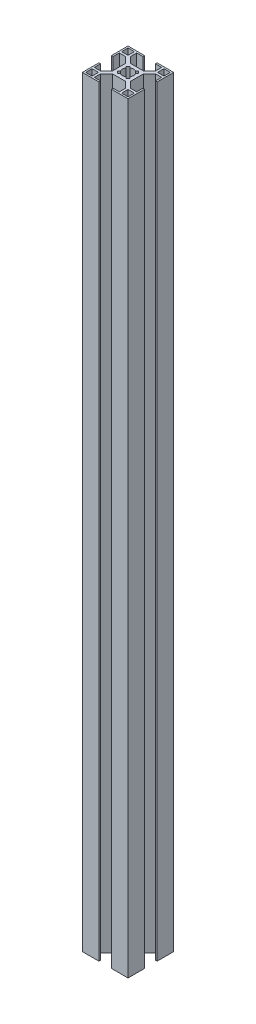
SolidWorks part; units mm, degrees
material "3.0255 (EN-AW 1350A)"
ref_plane "Alzado" through (0, 0, 0) normal (0, 0, 1) x (1, 0, 0)
ref_plane "Planta" through (0, 0, 0) normal (0, 1, 0) x (1, 0, 0)
ref_plane "Vista lateral" through (0, 0, 0) normal (1, 0, 0) x (0, 0, -1)
sketch "Croquis2" plane through (0, 0, 0) normal (0, 1, 0) x (1, 0, 0)
  line L0 (-12.6732, 23.1711) -> (-8.4732, 23.1711)
  line L1 (-37.3732, 24.2711) -> (-26.4982, 24.2711)
  line L2 (-37.3732, 24.2711) -> (-37.3732, 13.3961)
  line L3 (-37.3732, -5.7289) -> (-26.4982, -5.7289)
  line L4 (-7.3732, 24.2711) -> (-7.3732, 13.3961)
  line L5 (-30.5732, -4.6289) -> (-26.4982, -4.6289)
  line L6 (-30.5732, 23.1711) -> (-26.4982, 23.1711)
  line L7 (-36.2732, 5.1461) -> (-37.3732, 5.1461)
  line L8 (-8.4732, 23.1711) -> (-8.4732, 18.9711)
  line L9 (-36.2732, -4.6289) -> (-32.0732, -4.6289)
  line L10 (-36.2732, 23.1711) -> (-36.2732, 18.9711)
  line L11 (-36.2732, 23.1711) -> (-32.0732, 23.1711)
  line L12 (-32.0732, -0.4289) -> (-36.2732, -0.4289)
  line L15 (-8.4732, 18.9711) -> (-12.6732, 18.9711)
  line L16 (-12.6732, 23.1711) -> (-12.6732, 18.9711)
  line L17 (-32.0732, -0.4289) -> (-32.0732, -4.6289)
  line L19 (-36.2732, -0.4289) -> (-36.2732, -4.6289)
  line L21 (-32.0732, 23.1711) -> (-32.0732, 18.9711)
  line L22 (-32.0732, 18.9711) -> (-36.2732, 18.9711)
  line L24 (-8.4732, -0.4289) -> (-12.6732, -0.4289)
  line L25 (-8.4732, -0.4289) -> (-8.4732, -4.6289)
  line L26 (-8.4732, -4.6289) -> (-12.6732, -4.6289)
  line L27 (-12.6732, -0.4289) -> (-12.6732, -4.6289)
  line L28 (-26.5862, 3.3611) -> (-18.1603, 3.3611)
  line L29 (-16.4632, 13.4841) -> (-16.4632, 5.0582)
  line L30 (-26.5862, 15.1811) -> (-18.1603, 15.1811)
  line L31 (-28.2832, 13.4841) -> (-28.2832, 5.0582)
  line L32 (-28.2832, 15.1811) -> (-16.4632, 15.1811) construction
  line L33 (-28.2832, 3.3611) -> (-16.4632, 3.3611) construction
  line L34 (-7.3732, 5.1461) -> (-8.4732, 5.1461)
  line L35 (-7.3732, 13.3961) -> (-8.4732, 13.3961)
  line L36 (-26.4982, 24.2711) -> (-26.4982, 23.1711)
  line L37 (-18.2482, 24.2711) -> (-18.2482, 23.1711)
  line L38 (-36.2732, 13.3961) -> (-37.3732, 13.3961)
  line L39 (-19.1655, 11.0646) -> (-18.2482, 11.9819)
  line L40 (-36.2732, 5.1461) -> (-36.2732, 1.0711)
  line L41 (-36.2732, 23.1711) -> (-36.2732, -4.6289) construction
  line L42 (-37.3732, 5.1461) -> (-37.3732, -5.7289)
  line L43 (-37.3732, 24.2711) -> (-37.3732, -5.7289) construction
  line L44 (-18.2482, -4.6289) -> (-18.2482, -5.7289)
  line L46 (-8.4732, 5.1461) -> (-8.4732, 1.0711)
  line L47 (-8.4732, 23.1711) -> (-8.4732, -4.6289) construction
  line L48 (-7.3732, 5.1461) -> (-7.3732, -5.7289)
  line L49 (-7.3732, 24.2711) -> (-7.3732, -5.7289) construction
  line L51 (-25.084, 5.1461) -> (-24.1667, 6.0634)
  line L52 (-18.2482, -4.6289) -> (-14.1732, -4.6289)
  line L53 (-36.2732, -4.6289) -> (-8.4732, -4.6289) construction
  line L54 (-18.2482, -5.7289) -> (-7.3732, -5.7289)
  line L55 (-37.3732, -5.7289) -> (-7.3732, -5.7289) construction
  line L56 (-16.4632, 15.1811) -> (-16.4632, 3.3611) construction
  line L57 (-26.4982, 11.9819) -> (-25.5809, 11.0646)
  line L58 (-18.2482, 23.1711) -> (-14.1732, 23.1711)
  line L59 (-36.2732, 23.1711) -> (-8.4732, 23.1711) construction
  line L60 (-18.2482, 24.2711) -> (-7.3732, 24.2711)
  line L61 (-37.3732, 24.2711) -> (-7.3732, 24.2711) construction
  line L62 (-32.2703, 1.0711) -> (-36.2732, 1.0711)
  line L63 (-30.5732, 1.0711) -> (-37.7732, 1.0711) construction
  line L64 (-30.5732, 1.0711) -> (-30.5732, -6.1289) construction
  line L65 (-30.5732, -0.6259) -> (-30.5732, -4.6289)
  line L66 (-8.4732, 1.0711) -> (-12.4762, 1.0711)
  line L67 (-14.1732, -0.6259) -> (-14.1732, -4.6289)
  line L68 (-6.9732, 1.0711) -> (-6.9732, -6.1289) construction
  line L69 (-30.5732, -0.6259) -> (-26.5862, 3.3611)
  line L70 (-6.9732, 17.4711) -> (-14.1732, 17.4711) construction
  line L71 (-8.4732, 17.4711) -> (-12.4762, 17.4711)
  line L72 (-14.1732, 23.1711) -> (-14.1732, 19.1682)
  line L73 (-8.4732, 17.4711) -> (-8.4732, 13.3961)
  line L74 (-32.2703, 17.4711) -> (-36.2732, 17.4711)
  line L75 (-30.5732, 24.6711) -> (-30.5732, 17.4711) construction
  line L76 (-16.4632, 13.4841) -> (-12.4762, 17.4711)
  line L77 (-30.5732, 23.1711) -> (-30.5732, 19.1682)
  line L78 (-30.5732, -6.1289) -> (-37.7732, -6.1289) construction
  line L79 (-37.7732, 1.0711) -> (-37.7732, -6.1289) construction
  line L80 (-26.4982, -4.6289) -> (-26.4982, -5.7289)
  line L81 (-30.5732, 19.1682) -> (-26.5862, 15.1811)
  line L83 (-18.1603, 3.3611) -> (-14.1732, -0.6259)
  line L84 (-30.5732, 17.4711) -> (-37.7732, 17.4711) construction
  line L85 (-37.7732, 24.6711) -> (-37.7732, 17.4711) construction
  line L86 (-30.5732, 24.6711) -> (-37.7732, 24.6711) construction
  line L87 (-36.2732, 17.4711) -> (-36.2732, 13.3961)
  line L88 (-32.2703, 1.0711) -> (-28.2832, 5.0582)
  line L90 (-6.9732, -6.1289) -> (-14.1732, -6.1289) construction
  line L91 (-14.1732, 1.0711) -> (-14.1732, -6.1289) construction
  line L92 (-6.9732, 1.0711) -> (-14.1732, 1.0711) construction
  line L94 (-25.084, 13.3961) -> (-24.1667, 12.4788)
  line L95 (-19.1655, 7.4777) -> (-18.2482, 6.5603)
  line L96 (-20.5798, 6.0634) -> (-19.6624, 5.1461)
  line L97 (-14.1732, 24.6711) -> (-14.1732, 17.4711) construction
  line L98 (-6.9732, 24.6711) -> (-14.1732, 24.6711) construction
  line L99 (-6.9732, 24.6711) -> (-6.9732, 17.4711) construction
  line L100 (-16.4632, 5.0582) -> (-12.4762, 1.0711)
  line L101 (-26.4982, 6.5603) -> (-25.5809, 7.4777)
  line L104 (-28.2832, 15.1811) -> (-28.2832, 3.3611) construction
  line L105 (-18.1603, 15.1811) -> (-14.1732, 19.1682)
  line L106 (-32.2703, 17.4711) -> (-28.2832, 13.4841)
  line L111 (-20.5798, 12.4788) -> (-19.6624, 13.3961)
  line L114 (-26.4982, 6.5603) -> (-25.084, 5.1461)
  line L115 (-19.6624, 5.1461) -> (-18.2482, 6.5603)
  line L116 (-19.6624, 13.3961) -> (-18.2482, 11.9819)
  line L117 (-25.084, 13.3961) -> (-26.4982, 11.9819)
  line L119 (-32.0732, 23.1711) -> (-36.2732, 23.1711) construction
  line L120 (-8.4732, 23.1711) -> (-12.6732, 23.1711) construction
  line L121 (-32.0732, -4.6289) -> (-36.2732, -4.6289) construction
  line L122 (-8.4732, 23.1711) -> (-8.4732, 18.9711) construction
  line L123 (-36.2732, 23.1711) -> (-36.2732, 18.9711) construction
  arc A0 (-25.5809, 11.0646) -> (-25.5809, 7.4777) centre (-22.3732, 9.2711) ccw
  arc A1 (-20.5798, 12.4788) -> (-24.1667, 12.4788) centre (-22.3732, 9.2711) ccw
  arc A2 (-19.1655, 7.4777) -> (-19.1655, 11.0646) centre (-22.3732, 9.2711) ccw
  arc A3 (-24.1667, 6.0634) -> (-20.5798, 6.0634) centre (-22.3732, 9.2711) ccw
  dimension "D1" = 30
  dimension "D2" = 30
  dimension "D5" = 1.5
extrude "Saliente-Extruir1" add sketch "Croquis2" along normal blind 500
